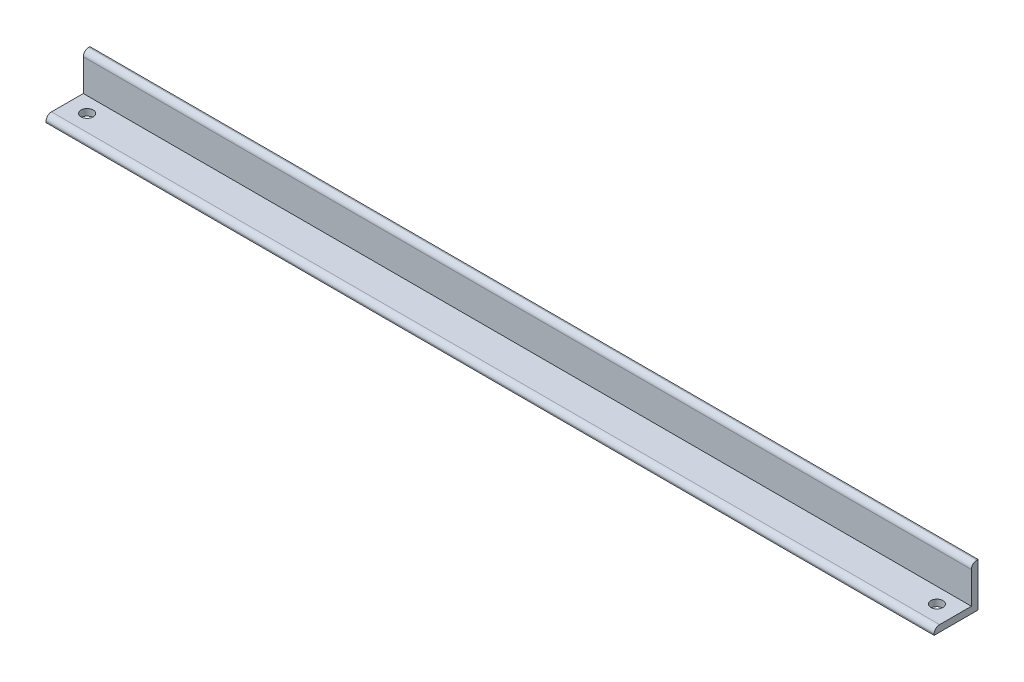
SolidWorks part; units mm, degrees
ref_plane "前视基准面" through (0, 0, 0) normal (0, 0, 1) x (1, 0, 0)
ref_plane "上视基准面" through (0, 0, 0) normal (0, 1, 0) x (1, 0, 0)
ref_plane "右视基准面" through (0, 0, 0) normal (1, 0, 0) x (0, 0, -1)
sketch "草图1" plane through (0, 0, 0) normal (0, 0, 1) x (1, 0, 0)
  line L1 (0, 0) -> (1619, 0)
  line L2 (0, 0) -> (0, 80)
  line L3 (0, 80) -> (1619, 80)
  line L4 (1619, 0) -> (1619, 80)
  dimension "D1" = 1619
  dimension "D2" = 80
extrude "拉伸1" add sketch "草图1" along normal blind 80
sketch "草图3" plane through (0, 0, 0) normal (-1, 0, 0) x (0, 0, 1)
  line L0 (80, 80) -> (80, 0) construction
  line L1 (12, 80) -> (80, 80)
  line L2 (12, 80) -> (12, 12)
  line L3 (12, 12) -> (80, 12)
  line L4 (80, 80) -> (80, 12)
  line L5 (80, 80) -> (0, 80) construction
  line L6 (80, 0) -> (0, 0) construction
  line L7 (0, 80) -> (0, 0) construction
  dimension "D1" = 12
  dimension "D2" = 12
extrude "拉伸2" cut sketch "草图3" against normal through all
fillet "圆角1" radius 10 2 edges at (809.5, 12, 80) (809.5, 80, 12)
sketch "草图7" plane through (0, 0, 0) normal (0, -1, 0) x (1, 0, 0)
  line L0 (0, 0) -> (1619, 0) construction
  line L1 (0, 80) -> (0, 0) construction
  circle A0 centre (35, 40) radius 11
  dimension "D1" = 40
  dimension "D3" = 22
  dimension "D2" = 35
extrude "拉伸5" cut sketch "草图7" against normal through all
pattern_linear "阵列(线性)3" count 2 spacing 1549.0126 along (1, 0, 0) of "拉伸5"
